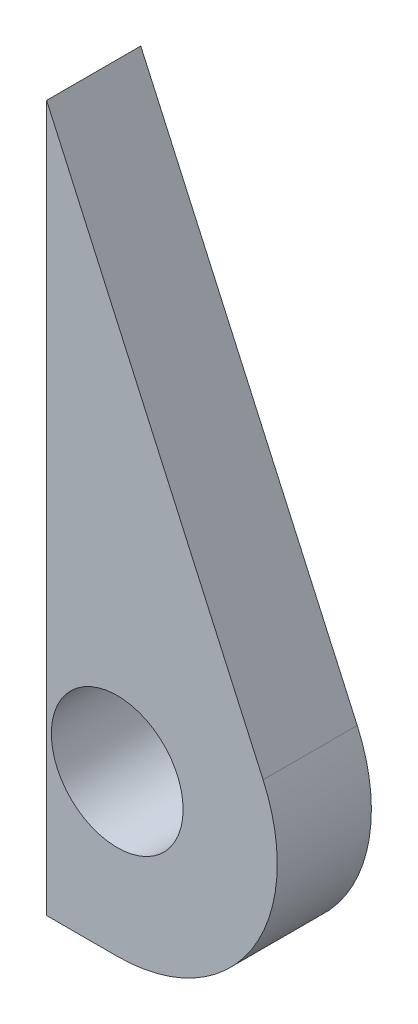
SolidWorks part; units mm, degrees
ref_plane "Front Plane" through (0, 0, 0) normal (0, 0, 1) x (1, 0, 0)
ref_plane "Top Plane" through (0, 0, 0) normal (0, 1, 0) x (1, 0, 0)
ref_plane "Right Plane" through (0, 0, 0) normal (1, 0, 0) x (0, 0, -1)
sketch "Sketch1" plane through (0, 0, 0) normal (0, 0, 1) x (1, 0, 0)
  line L0 (-1.5, 16.1222) -> (-1.5, -6.5252) construction
  line L1 (0, 0) -> (-1.5, 0) construction
  line L2 (0, 0) -> (1.4, 0) construction
  line L3 (1.4, 0) -> (3.4, 0) construction
  line L4 (-1.5, -3.4) -> (-1.5, -1.4)
  line L5 (-1.5, 11.6) -> (3.0996, 1.3974)
  line L6 (0, -3.4) -> (-1.5, -3.4)
  line L7 (-1.5, 3.6) -> (-3.5, 3.6) construction
  line L8 (-3.5, 3.6) -> (-3.5, -1.4) construction
  line L9 (-3.5, -1.4) -> (-1.5, -1.4) construction
  line L10 (-1.5, 3.6) -> (-1.5, 11.6)
  line L11 (-1.5, 3.6) -> (-1.5, -1.4)
  circle A0 centre (0, 0) radius 1.4
  arc A1 (0, -3.4) -> (3.0996, 1.3974) centre (0, 0) ccw
  dimension "D1" = 2.8
  dimension "D2" = 1.5
  dimension "D3" = 2
  dimension "D4" = 15
  dimension "D5" = 2
  dimension "D6" = 2
  dimension "D7" = 5
extrude "Boss-Extrude1" add sketch "Sketch1" along normal blind 2
